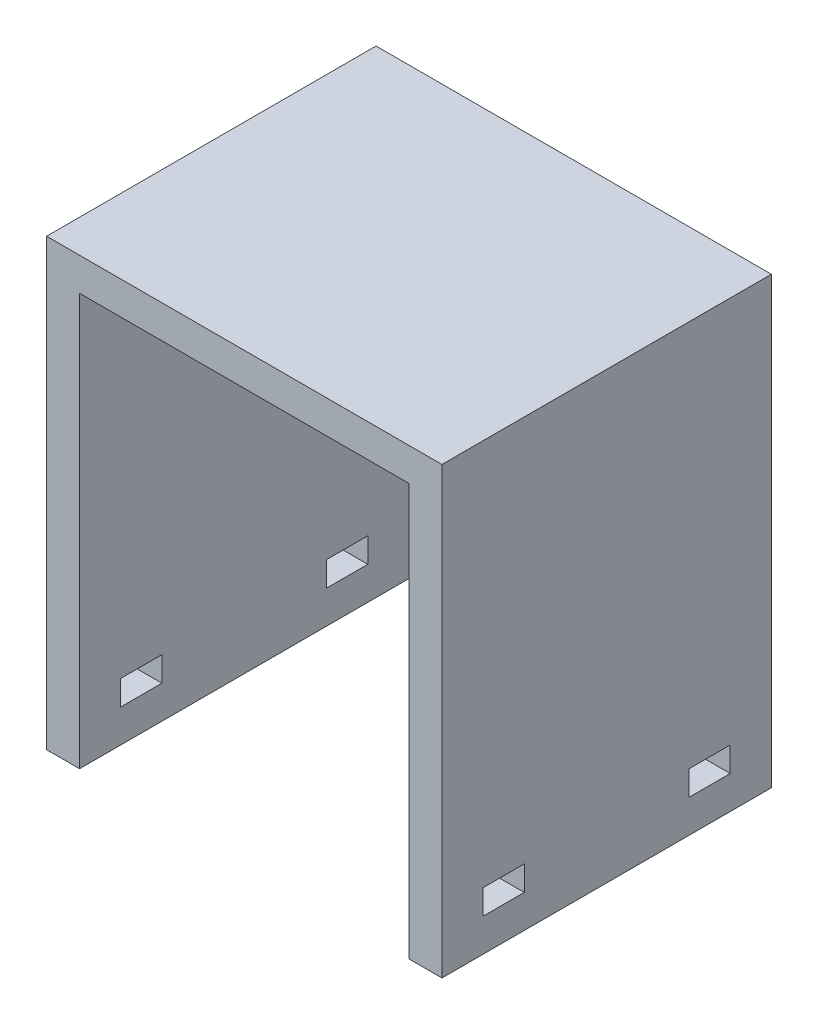
SolidWorks part; units mm, degrees
ref_plane "Front Plane" through (0, 0, 0) normal (0, 0, 1) x (1, 0, 0)
ref_plane "Top Plane" through (0, 0, 0) normal (0, 1, 0) x (1, 0, 0)
ref_plane "Right Plane" through (0, 0, 0) normal (1, 0, 0) x (0, 0, -1)
sketch "Sketch1" plane through (0, 0, 0) normal (0, 0, 1) x (1, 0, 0)
  line L0 (55.88, 55.88) -> (55.88, -12.7)
  line L1 (55.88, 55.88) -> (-5.08, 55.88)
  line L2 (0, 50.8) -> (0, -12.7)
  line L3 (0, -12.7) -> (-5.08, -12.7)
  line L4 (-5.08, 55.88) -> (-5.08, -12.7)
  line L5 (55.88, -12.7) -> (50.8, -12.7)
  line L6 (50.8, -12.7) -> (50.8, 50.8)
  line L7 (50.8, 50.8) -> (0, 50.8)
  line L8 (50.8, 50.8) -> (0, 50.8) construction
  line L9 (0, 50.8) -> (0, 0) construction
  line L10 (0, 0) -> (50.8, 0) construction
  line L11 (50.8, 0) -> (50.8, 50.8) construction
  dimension "D1" = 50.8
  dimension "D2" = 50.8
  dimension "D3" = 12.7
  dimension "D4" = 5.08
  dimension "D5" = 5.08
extrude "Boss-Extrude1" add sketch "Sketch1" along normal blind 50.8
sketch "Sketch2" plane through (-5.08, 0, 0) normal (-1, 0, 0) x (0, 0, 1)
  line L1 (6.35, -3.81) -> (12.7, -3.81)
  line L2 (6.35, -3.81) -> (6.35, -7.62)
  line L3 (6.35, -7.62) -> (12.7, -7.62)
  line L4 (12.7, -3.81) -> (12.7, -7.62)
  line L5 (38.1, -3.81) -> (44.45, -3.81)
  line L6 (38.1, -3.81) -> (38.1, -7.62)
  line L7 (38.1, -7.62) -> (44.45, -7.62)
  line L8 (44.45, -3.81) -> (44.45, -7.62)
  line L9 (0, -12.7) -> (6.35, -12.7) construction
  line L10 (0, -12.7) -> (0, -7.62) construction
  line L11 (0, -7.62) -> (6.35, -7.62) construction
  line L12 (6.35, -12.7) -> (6.35, -7.62) construction
  line L13 (50.8, -12.7) -> (44.45, -12.7) construction
  line L14 (50.8, -12.7) -> (50.8, -7.62) construction
  line L15 (50.8, -7.62) -> (44.45, -7.62) construction
  line L16 (44.45, -12.7) -> (44.45, -7.62) construction
  point P13 (23.9818, -7.3157)
  point P17 (6.1976, -9.3837)
  point P18 (14.9073, -6.5129)
  dimension "D1" = 6.35
  dimension "D2" = 3.81
  dimension "D3" = 6.35
  dimension "D4" = 5.08
extrude "Cut-Extrude1" cut sketch "Sketch2" against normal through all
